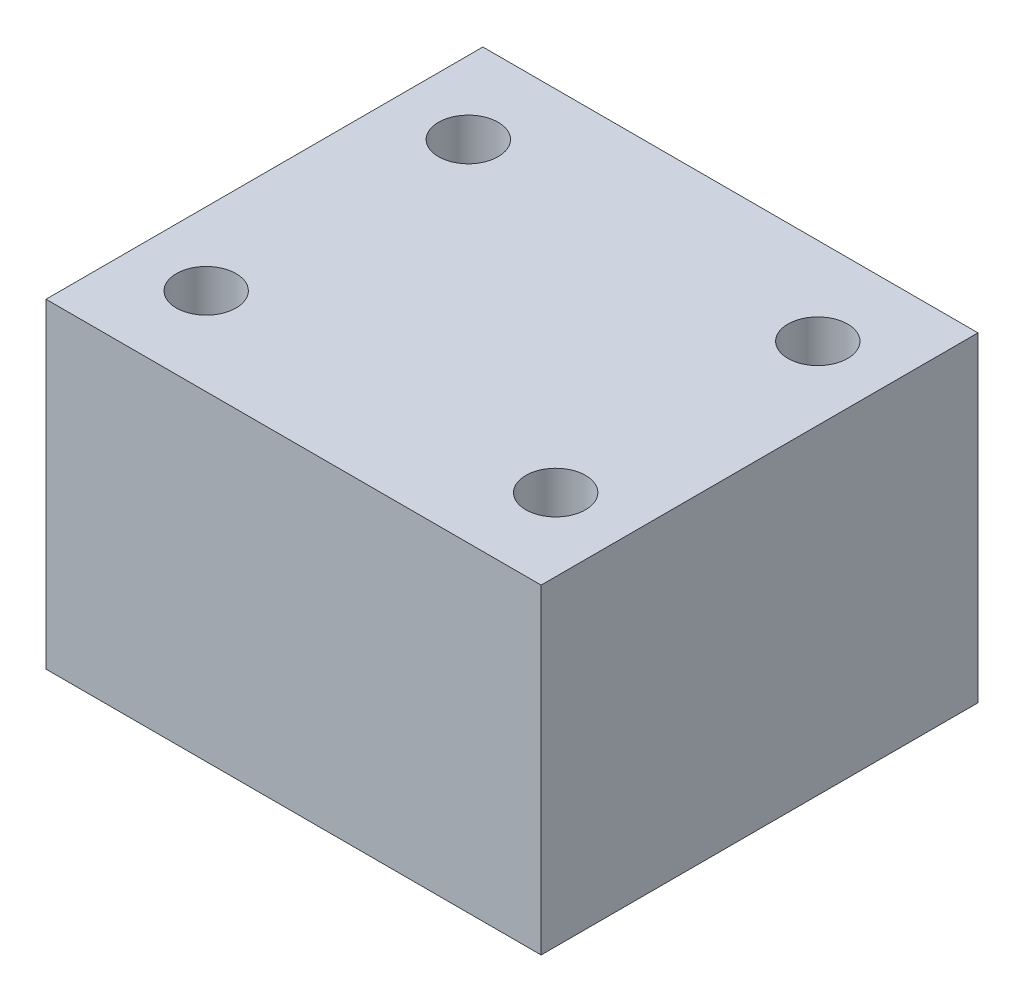
SolidWorks part; units mm, degrees
ref_plane "Front Plane" through (0, 0, 0) normal (0, 0, 1) x (1, 0, 0)
ref_plane "Top Plane" through (0, 0, 0) normal (0, 1, 0) x (1, 0, 0)
ref_plane "Right Plane" through (0, 0, 0) normal (1, 0, 0) x (0, 0, -1)
sketch "Sketch2" plane through (0, 0, 0) normal (0, 0, 1) x (1, 0, 0)
  line L0 (0, 0) -> (34, 0)
  line L1 (34, 0) -> (34, 22)
  line L2 (34, 22) -> (0, 22)
  line L3 (0, 22) -> (0, 0)
  dimension "D1" = 22
  dimension "D2" = 34
extrude "Boss-Extrude1" add sketch "Sketch2" against normal blind 30
sketch "Sketch3" plane through (0, 22, 0) normal (0, 1, 0) x (1, 0, 0)
  line L0 (0, 30) -> (0, 0) construction
  line L1 (34, 30) -> (34, 0) construction
  line L2 (34, 0) -> (0, 0) construction
  circle A0 centre (29, 6) radius 2.05
  circle A1 centre (5, 6) radius 2.05
  circle A2 centre (5, 24) radius 2.05
  circle A3 centre (29, 24) radius 2.05
  dimension "D1" = 4.1
  dimension "D2" = 4.1
  dimension "D3" = 4.1
  dimension "D4" = 4.1
  dimension "D5" = 5
  dimension "D6" = 5
  dimension "D7" = 24
  dimension "D8" = 18
  dimension "D9" = 6
  dimension "D10" = 5
  dimension "D11" = 5
  dimension "D12" = 18
extrude "Cut-Extrude1" cut sketch "Sketch3" against normal blind 30
